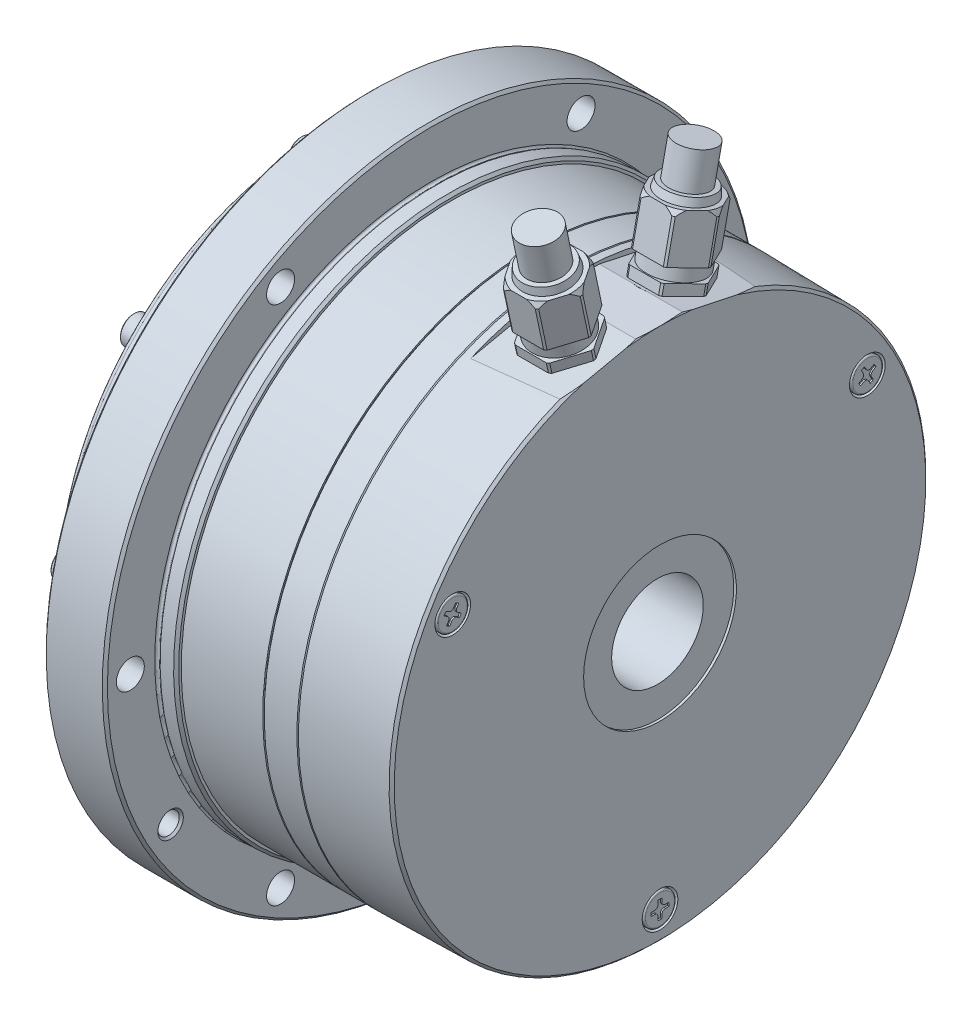
SolidWorks part; units mm, degrees
material "6063-T1"
ref_plane "Front Plane" through (0, 0, 0) normal (0, 0, 1) x (1, 0, 0)
ref_plane "Top Plane" through (0, 0, 0) normal (0, 1, 0) x (1, 0, 0)
ref_plane "Right Plane" through (0, 0, 0) normal (1, 0, 0) x (0, 0, -1)
sketch "Sketch1" plane through (0, 0, 0) normal (0, 0, 1) x (1, 0, 0)
  line L0 (-21, 0) -> (-21, 34.5)
  line L1 (-21, 34.5) -> (-20.5, 35)
  line L2 (-20.5, 35) -> (-15.5, 35)
  line L3 (-15.5, 35) -> (-15.5, 39.5)
  line L4 (-15.5, 39.5) -> (-15, 39.5)
  line L5 (-15, 39.5) -> (-15, 41.7)
  line L6 (-14.2, 42.5) -> (-10.5, 42.5)
  line L7 (-10.5, 42.5) -> (-10.5, 50)
  line L8 (-9.5, 51) -> (-7, 51)
  line L9 (-7, 51) -> (-7, 50)
  line L10 (-7, 50) -> (-6.6, 50)
  line L11 (-6.6, 50) -> (-6.6, 52.2)
  line L12 (-6.6, 52.2) -> (-6.3, 52.5)
  line L13 (-6.3, 52.5) -> (-0.854, 52.5)
  line L14 (-0.854, 52.5) -> (-0.5998, 52.3535)
  line L15 (39, 52.7) -> (39, 53)
  line L16 (0, 0) -> (-21, 0)
  line L17 (0, 0) -> (-21, 0) construction
  line L18 (0, 52.7) -> (0, 63.5)
  line L19 (0, 63.5) -> (0.5, 64)
  line L20 (0.5, 64) -> (11.5, 64)
  line L21 (11.5, 64) -> (12, 63.5)
  line L22 (12, 63.5) -> (12, 54.2)
  line L23 (12, 0) -> (0, 0)
  line L24 (12, 0) -> (0, 0) construction
  line L25 (12.5998, 53.8535) -> (12.854, 54)
  line L26 (12.854, 54) -> (15.5, 54)
  line L27 (15.5, 54) -> (16, 53.5)
  line L28 (16, 53.5) -> (16, 53)
  line L29 (16, 0) -> (12, 0)
  line L30 (16, 0) -> (12, 0) construction
  line L31 (16, 53) -> (32, 53)
  line L32 (32, 53) -> (32, 52.7)
  line L33 (32, 0) -> (16, 0)
  line L34 (32, 0) -> (16, 0) construction
  line L35 (32, 52.7) -> (32.3, 53)
  line L36 (32.3, 53) -> (38.7, 53)
  line L37 (38.7, 53) -> (39, 52.7)
  line L39 (39, 0) -> (32, 0)
  line L40 (39, 0) -> (32, 0) construction
  line L41 (39, 53) -> (56.5001, 52.6945)
  line L42 (56.5001, 52.6945) -> (57, 52.1858)
  line L43 (57, 52.1858) -> (57, 0)
  line L44 (57, 0) -> (39, 0)
  line L45 (57, 0) -> (39, 0) construction
  arc A0 (-15, 41.7) -> (-14.2, 42.5) centre (-14.2, 41.7) cw
  arc A1 (-10.5, 50) -> (-9.5, 51) centre (-9.5, 50) cw
  arc A2 (-0.5998, 52.3535) -> (0, 52.7) centre (-0.4, 52.7) ccw
  arc A3 (12, 54.2) -> (12.5998, 53.8535) centre (12.4, 54.2) ccw
revolve "Main Body" add sketch "Sketch1" angle 360 about L17
sketch "Sketch7" plane through (57, 0, 0) normal (1, 0, 0) x (0, 0, -1)
  line L0 (-53.056, 57.2194) -> (-49.9373, 42.5472)
  line L1 (-49.9373, 42.5472) -> (-4.5904, 52.186)
  line L2 (-4.5904, 52.186) -> (4.5904, 52.186)
  line L3 (4.5904, 52.186) -> (49.9373, 42.5472)
  line L4 (49.9373, 42.5472) -> (53.056, 57.2194)
  line L5 (53.056, 57.2194) -> (0, 68.4968)
  line L6 (0, 68.4968) -> (-53.056, 57.2194)
extrude "Leads Faces Cut" cut sketch "Sketch7" against normal blind 16.5
ref_plane "Encoder Lead Plane" through (0, 0, 0) normal (0, -0.2079, -0.9781) x (-1, 0, 0)
sketch "Sketch8" plane through (0, 0, 0) normal (0, -0.2079, -0.9781) x (-1, 0, 0)
  line L0 (-48.5, 47) -> (-55, 47)
  line L1 (-55, 47) -> (-55, 54)
  line L2 (-55, 54) -> (-54, 54)
  line L3 (-54, 54) -> (-54, 56.5)
  line L4 (-54, 56.5) -> (-55, 56.5)
  line L5 (-55, 56.5) -> (-55, 64.5)
  line L6 (-55, 64.5) -> (-54.4457, 65.5)
  line L7 (-54.4457, 65.5) -> (-53.5, 65.5)
  line L8 (-53.5, 65.5) -> (-53.2084, 67)
  line L9 (-53.2084, 67) -> (-52.3, 67)
  line L10 (-52.3, 67) -> (-52.3, 74)
  line L11 (-52.3, 74) -> (-48.5, 74)
  line L12 (-48.5, 74) -> (-48.5, 47)
  line L13 (-48.5, 74) -> (-48.5, 47) construction
revolve "Encoder Lead Plug" add sketch "Sketch8" angle 360 about L13
sketch "Sketch9" plane through (0, 65.5359, -13.9301) normal (0, 0.9781, -0.2079) x (1, 0, 0)
  line L0 (41.5, -10) -> (58.5, -10)
  line L1 (58.5, -10) -> (58.5, 10)
  line L2 (58.5, 10) -> (41.5, 10)
  line L3 (41.5, 10) -> (41.5, -10)
  line L4 (51.8198, -5.75) -> (55.1395, 0)
  line L5 (55.1395, 0) -> (51.8198, 5.75)
  line L6 (51.8198, 5.75) -> (45.1802, 5.75)
  line L7 (45.1802, 5.75) -> (41.8605, 0)
  line L8 (41.8605, 0) -> (45.1802, -5.75)
  line L9 (45.1802, -5.75) -> (51.8198, -5.75)
extrude "Encoder hex Cut" cut sketch "Sketch9" against normal blind 15
ref_plane "Motor Lead Plane" through (0, 0, 0) normal (0, 0.2079, -0.9781) x (-1, 0, 0)
sketch "Sketch10" plane through (0, 0, 0) normal (0, 0.2079, -0.9781) x (-1, 0, 0)
  line L0 (-48.5, 47) -> (-55, 47)
  line L1 (-55, 47) -> (-55, 54)
  line L2 (-55, 54) -> (-54, 54)
  line L3 (-54, 54) -> (-54, 56.5)
  line L4 (-54, 56.5) -> (-55, 56.5)
  line L5 (-55, 56.5) -> (-55, 64.5)
  line L6 (-55, 64.5) -> (-54.4457, 65.5)
  line L7 (-54.4457, 65.5) -> (-53.5, 65.5)
  line L8 (-53.5, 65.5) -> (-53.2084, 67)
  line L9 (-53.2084, 67) -> (-52.3, 67)
  line L10 (-52.3, 67) -> (-52.3, 74)
  line L11 (-52.3, 74) -> (-48.5, 74)
  line L12 (-48.5, 74) -> (-48.5, 47)
  line L13 (-48.5, 74) -> (-48.5, 47) construction
revolve "Motor Lead Plug" add sketch "Sketch10" angle 360 about L13
sketch "Sketch11" plane through (0, 65.5359, 13.9301) normal (0, 0.9781, 0.2079) x (1, 0, 0)
  line L0 (41.5, -10) -> (58.5, -10)
  line L1 (58.5, -10) -> (58.5, 10)
  line L2 (58.5, 10) -> (41.5, 10)
  line L3 (41.5, 10) -> (41.5, -10)
  line L4 (51.8198, -5.75) -> (55.1395, 0)
  line L5 (55.1395, 0) -> (51.8198, 5.75)
  line L6 (51.8198, 5.75) -> (45.1802, 5.75)
  line L7 (45.1802, 5.75) -> (41.8605, 0)
  line L8 (41.8605, 0) -> (45.1802, -5.75)
  line L9 (45.1802, -5.75) -> (51.8198, -5.75)
extrude "Motor Hex Cut" cut sketch "Sketch11" against normal blind 15
hole_wizard "Ø5.5 (5.5) Diameter Hole1" positions "Sketch58" profile "Sketch57" hole size "Ø5.5" standard "ANSI Metric"
sketch "Sketch58" plane through (0, 0, 0) normal (-1, 0, 0) x (0, 0, 1)
  line L0 (-1000, 0) -> (49000, 0) construction
  circle A0 centre (0, 0) radius 59 construction
  point P9 (59, 0)
  point P16 (29.5, -51.0955)
  point P17 (-29.5, -51.0955)
  point P18 (-59, 0)
  point P19 (-29.5, 51.0955)
  point P20 (29.5, 51.0955)
  point P21 (0, 0)
  dimension "D1" = 118
  dimension "D2" = 6
sketch "Sketch57" plane through (0, 0, 59) normal (0, 1, 0) x (0, 0, 1)
  line L0 (0, 0) -> (0, 57)
  line L1 (0, 57) -> (2.75, 57)
  line L2 (2.75, 57) -> (2.75, 0)
  line L5 (2.75, 0) -> (0, 0)
  line L11 (0, -6.35) -> (0, 107.95) construction
  dimension "Thru Hole Dia." = 5.5
  dimension "Thru Hole Depth" = 57
hole_wizard "Tap Drill for M5x0.8 Tap3" positions "Sketch60" profile "Sketch59" hole size "M5x0.8" standard "ANSI Metric" end condition up to next
sketch "Sketch60" plane through (0, 0, 0) normal (-1, 0, 0) x (0, 0, 1)
  line L0 (-1000, 0) -> (49000, 0) construction
  line L1 (0, 0) -> (-43301.2702, 25000) construction
  circle A0 centre (0, 0) radius 59 construction
  point P0 (51.0955, -29.5)
  point P4 (-51.0955, 29.5)
  dimension "D1" = 30
sketch "Sketch59" plane through (0, -29.5, 51.0955) normal (0, 1, 0) x (0, 0, 1)
  line L0 (0, 0) -> (0, 12)
  line L1 (0, 12) -> (2.5, 12)
  line L2 (2.1, 11.6) -> (2.1, 0.4)
  line L3 (2.1, 0.4) -> (2.5, 0)
  line L5 (2.5, 0) -> (0, 0)
  line L6 (-2.1, 0.4) -> (-2.5, 0) construction
  line L7 (2.5, 12) -> (2.1, 11.6)
  line L8 (-2.5, 12) -> (-2.1, 11.6) construction
  line L11 (0, -6.35) -> (0, 107.95) construction
  dimension "Thru Hole Dia." = 4.2
  dimension "Thru Hole Depth" = 12
  dimension "Near C'Sink Dia." = 5
  dimension "Near C'Sink Angle" = 90
  dimension "Far C'Sink Dia." = 5
  dimension "Far C'Sink Angle" = 90
cosmetic thread "Cosmetic Thread13" parameters "D2"=5
cosmetic thread "Cosmetic Thread14" parameters "D2"=5
sketch "Sketch26" plane through (0, 0, 0) normal (0, 0, 1) x (1, 0, 0)
  line L0 (-21, 0) -> (-21, 20)
  line L1 (-21, 20) -> (-20.5, 20)
  line L2 (-20.5, 20) -> (-20.5, 12.5)
  line L3 (-20.5, 12.5) -> (-17.5, 12.5)
  line L4 (-17.5, 12.5) -> (-17.5, 9)
  line L5 (-17.5, 9) -> (56.5, 9)
  line L6 (56.5, 9) -> (56.5, 15)
  line L7 (56.5, 15) -> (57, 15)
  line L8 (57, 15) -> (57, 0)
  line L9 (57, 0) -> (-21, 0)
  line L10 (57, 0) -> (-21, 0) construction
revolve "Cut-Revolve12" cut sketch "Sketch26" angle 360 about L10
sketch "Sketch20" plane through (0, 0, 0) normal (0, 0, 1) x (1, 0, 0)
  line L0 (57, -47) -> (57, -44.15)
  line L1 (56.7, -43.85) -> (54, -43.85)
  line L2 (54, -43.85) -> (54, -43.5)
  line L3 (54, -43.5) -> (59, -43.5)
  line L4 (59, -43.5) -> (59, -47)
  line L5 (59, -47) -> (57, -47)
  line L6 (59, -47) -> (57, -47) construction
  arc A0 (57, -44.15) -> (56.7, -43.85) centre (56.7, -44.15) ccw
revolve "Back Screrw" cut sketch "Sketch20" angle 360 about L6
sketch "Sketch23" plane through (57, 0, 0) normal (1, 0, 0) x (0, 0, -1)
  line L0 (-1.75, -47.35) -> (-1.05, -47.35)
  line L1 (-0.35, -48.05) -> (-0.35, -48.75)
  line L2 (-0.35, -48.75) -> (0.35, -48.75)
  line L3 (0.35, -48.75) -> (0.35, -48.05)
  line L4 (1.05, -47.35) -> (1.75, -47.35)
  line L5 (1.75, -47.35) -> (1.75, -46.65)
  line L6 (1.75, -46.65) -> (1.05, -46.65)
  line L7 (0.35, -45.95) -> (0.35, -45.25)
  line L8 (0.35, -45.25) -> (-0.35, -45.25)
  line L9 (-0.35, -45.25) -> (-0.35, -45.95)
  line L10 (-1.05, -46.65) -> (-1.75, -46.65)
  line L11 (-1.75, -46.65) -> (-1.75, -47.35)
  arc A0 (-1.05, -47.35) -> (-0.35, -48.05) centre (-1.05, -48.05) cw
  arc A1 (0.35, -48.05) -> (1.05, -47.35) centre (1.05, -48.05) cw
  arc A2 (1.05, -46.65) -> (0.35, -45.95) centre (1.05, -45.95) cw
  arc A3 (-0.35, -45.95) -> (-1.05, -46.65) centre (-1.05, -45.95) cw
extrude "Back Screw Star" cut sketch "Sketch23" against normal blind 0.3
pattern_circular "CirPattern Back Screw" count 3 over 360 about axis through (0, 0, 0) along (1, 0, 0) of "Back Screrw", "Back Screw Star"
sketch "Sketch27" plane through (-21, 0, 0) normal (-1, 0, 0) x (0, 0, 1)
  line L0 (-8.5, -6.6395) -> (-1.5, -10.681)
  line L1 (1.5, -10.681) -> (8.5, -6.6395)
  line L2 (10, -4.0415) -> (10, 4.0415)
  line L3 (8.5, 6.6395) -> (1.5, 10.681)
  line L4 (-1.5, 10.681) -> (-8.5, 6.6395)
  line L5 (-10, 4.0415) -> (-10, -4.0415)
  arc A0 (-10, -4.0415) -> (-8.5, -6.6395) centre (-7, -4.0415) ccw
  arc A1 (-1.5, -10.681) -> (1.5, -10.681) centre (0, -8.0829) ccw
  arc A2 (8.5, -6.6395) -> (10, -4.0415) centre (7, -4.0415) ccw
  arc A3 (10, 4.0415) -> (8.5, 6.6395) centre (7, 4.0415) ccw
  arc A4 (1.5, 10.681) -> (-1.5, 10.681) centre (0, 8.0829) ccw
  arc A5 (-8.5, 6.6395) -> (-10, 4.0415) centre (-7, 4.0415) ccw
extrude "Hex Cut" cut sketch "Sketch27" against normal blind 14.4
ref_plane "Plane M4 Cap Screws" through (-13.5, 0, 0) normal (1, 0, 0) x (0, 0, -1)
sketch "Sketch28" plane through (0, 0, 0) normal (0, 0, 1) x (1, 0, 0)
  line L0 (-13.5, 46.5) -> (-13.5, 49.05)
  line L1 (-13.5, 49.05) -> (-13.3, 49.25)
  line L2 (-13.3, 49.25) -> (-10.5, 49.25)
  line L3 (-10.5, 49.25) -> (-10.5, 46.5)
  line L4 (-10.5, 46.5) -> (-13.5, 46.5)
  line L5 (-10.5, 46.5) -> (-13.5, 46.5) construction
revolve "M4 Cap Screw Head" add sketch "Sketch28" angle 360 about L5
sketch "Sketch36" plane through (-13.5, 0, 0) normal (1, 0, 0) x (0, 0, -1)
  line L0 (-1.25, 45.7783) -> (0, 45.0566)
  line L1 (0, 45.0566) -> (1.25, 45.7783)
  line L2 (1.25, 45.7783) -> (1.25, 47.2217)
  line L3 (1.25, 47.2217) -> (0, 47.9434)
  line L4 (0, 47.9434) -> (-1.25, 47.2217)
  line L5 (-1.25, 47.2217) -> (-1.25, 45.7783)
extrude "Hex Hole M4 Cap Screw" cut sketch "Sketch36" along normal blind 2
pattern_circular "CirPattern For M4 Cap" count 8 over 360 about axis through (0, 0, 0) along (1, 0, 0) of "M4 Cap Screw Head", "Hex Hole M4 Cap Screw"
hole_wizard "CBORE for M6 SHCS1" positions "Sketch56" profile "Sketch55" counterbore size "M6" standard "ANSI Metric"
sketch "Sketch56" plane through (-21, 0, 0) normal (-1, 0, 0) x (0, 0, 1)
  line L0 (-1000, 0) -> (49000, 0) construction
  circle A0 centre (0, 0) radius 30 construction
  point P0 (30, 0)
  point P17 (-15, -25.9808)
  point P18 (-15, 25.9808)
  point P19 (0, 0)
  dimension "D1" = 60
  dimension "D2" = 3
sketch "Sketch55" plane through (-21, 0, 30) normal (0, 1, 0) x (0, 0, 1)
  line L0 (0, 0) -> (0, 6)
  line L1 (0, 6) -> (3.05, 6)
  line L2 (3.05, 6) -> (3.05, 0.5)
  line L3 (3.05, 0.5) -> (4, 0.5)
  line L4 (4, 0.5) -> (4, 0)
  line L5 (4, 0) -> (0, 0)
  line L10 (0, 6) -> (-3.05, 6) construction
  line L11 (0, -6.35) -> (0, 107.95) construction
  dimension "Hole Dia." = 6.1
  dimension "Hole Depth" = 6
  dimension "C'Bore Dia." = 8
  dimension "C'Bore Depth" = 0.5
  dimension "Drill Angle" = 180
hole_wizard "Tap Drill for M5x0.8 Tap2" positions "Sketch54" profile "Sketch53" hole size "M5x0.8" standard "ANSI Metric"
sketch "Sketch54" plane through (-21, 0, 0) normal (-1, 0, 0) x (0, 0, 1)
  line L0 (0, -1000) -> (0, 49000) construction
  circle A0 centre (0, 0) radius 30 construction
  point P12 (0, 30)
  point P19 (25.9808, 15)
  point P20 (25.9808, -15)
  point P21 (0, -30)
  point P22 (-25.9808, -15)
  point P23 (-25.9808, 15)
  point P24 (0, 0)
  dimension "D1" = 60
  dimension "D2" = 6
sketch "Sketch53" plane through (-21, 30, 0) normal (0, 1, 0) x (0, 0, 1)
  line L0 (0, 0) -> (0, 9.2618)
  line L1 (0, 9.2618) -> (2.1, 8)
  line L2 (2.1, 8) -> (2.1, 0.4)
  line L3 (2.1, 0.4) -> (2.5, 0)
  line L5 (2.5, 0) -> (0, 0)
  line L6 (-2.1, 0.4) -> (-2.5, 0) construction
  line L10 (0, 9.2618) -> (-2.1, 8) construction
  line L11 (0, -6.35) -> (0, 107.95) construction
  dimension "Hole Dia." = 4.2
  dimension "Hole Depth" = 8
  dimension "Near C'Sink Dia." = 5
  dimension "Near C'Sink Angle" = 90
  dimension "Drill Angle" = 118
cosmetic thread "Cosmetic Thread7" parameters "D2"=5
cosmetic thread "Cosmetic Thread8" parameters "D2"=5
cosmetic thread "Cosmetic Thread9" parameters "D2"=5
cosmetic thread "Cosmetic Thread10" parameters "D2"=5
cosmetic thread "Cosmetic Thread11" parameters "D2"=5
cosmetic thread "Cosmetic Thread12" parameters "D2"=5
scale "Scale1" scale about centroid uniform scaling yes scale factor 0.8
